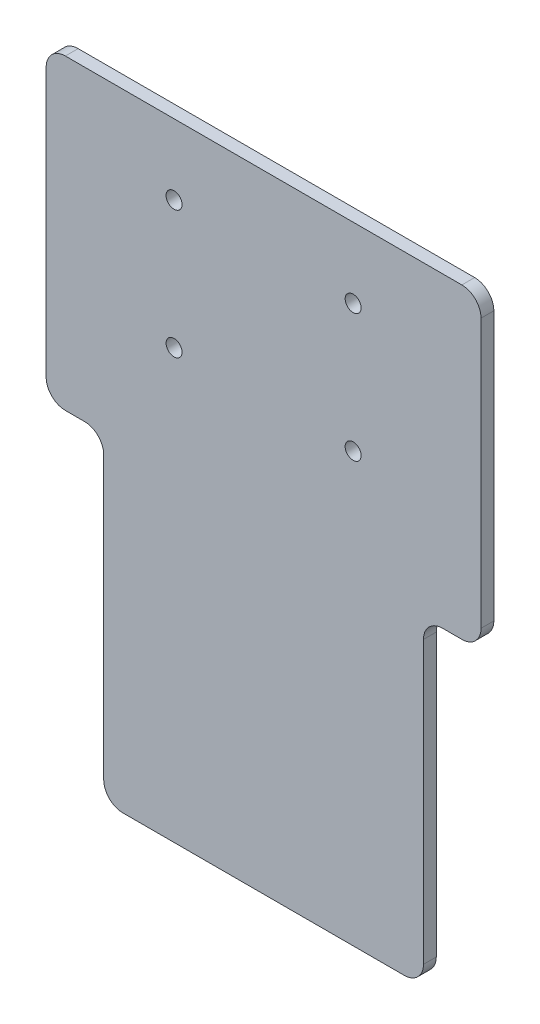
SolidWorks part; units mm, degrees
material "6063-T5"
ref_plane "前视基准面" through (0, 0, 0) normal (0, 0, 1) x (1, 0, 0)
ref_plane "上视基准面" through (0, 0, 0) normal (0, 1, 0) x (1, 0, 0)
ref_plane "右视基准面" through (0, 0, 0) normal (1, 0, 0) x (0, 0, -1)
sketch "草图1" plane through (0, 0, 0) normal (0, 0, 1) x (1, 0, 0)
  line L0 (34, 58) -> (34, 0) construction
  line L1 (0, 0) -> (68, 0)
  line L2 (0, 0) -> (0, 58)
  line L3 (0, 58) -> (68, 58)
  line L4 (68, 0) -> (68, 58)
  circle A0 centre (48, 27) radius 1.25
  circle A1 centre (20, 27) radius 1.25
  circle A2 centre (48, 47) radius 1.25
  circle A3 centre (20, 47) radius 1.25
  dimension "D3" = 2.5
  dimension "D4" = 28
  dimension "D5" = 27
  dimension "D7" = 20
  dimension "D8" = 2.5
  dimension "D1" = 68
  dimension "D2" = 58
extrude "凸台-拉伸1" add sketch "草图1" along normal blind 2
cosmetic thread "装饰螺纹线1" parameters "D2"=5
cosmetic thread "装饰螺纹线2" parameters "D2"=5
cosmetic thread "装饰螺纹线3" parameters "D2"=4
cosmetic thread "装饰螺纹线4" parameters "D2"=4
sketch "草图2" plane through (68, 0, 0) normal (1, 0, 0) x (0, 0, -1)
  line L0 (0, 0) -> (0, -40)
  line L1 (0, -40) -> (-2, -40)
  line L2 (-2, -40) -> (-2, 0)
  line L5 (0, 0) -> (0, 58) construction
  line L6 (-2, 0) -> (-2, 58) construction
  line L7 (0, 0) -> (-2, 0)
  dimension "D1" = 180
  dimension "D2" = 180
  dimension "D3" = 40
extrude "凸台-拉伸2" add sketch "草图2" against normal up to surface (68 mm away) up to face at (0, 29, 1)
sketch "草图3" plane through (0, 0, 2) normal (0, 0, 1) x (1, 0, 0)
  line L0 (0, 10) -> (9, 10)
  line L2 (0, 58) -> (0, -40) construction
  line L4 (9, 10) -> (9, -40)
  line L5 (0, -40) -> (68, -40) construction
  line L6 (0, 10) -> (0, -40)
  line L7 (0, -40) -> (9, -40)
  line L8 (68, -40) -> (68, 58) construction
  line L9 (68, 10) -> (59, 10)
  line L10 (68, 10) -> (68, -40)
  line L11 (68, -40) -> (59, -40)
  line L12 (59, 10) -> (59, -40)
  dimension "D1" = 9
  dimension "D2" = 50
  dimension "D3" = 9
extrude "切除-拉伸1" cut sketch "草图3" against normal blind 10
fillet "圆角1" radius 3 8 edges at (9, -40, 1) (59, -40, 1) (68, 58, 1) (0, 58, 1) (59, 10, 1) (9, 10, 1) (0, 10, 1) (68, 10, 1)
